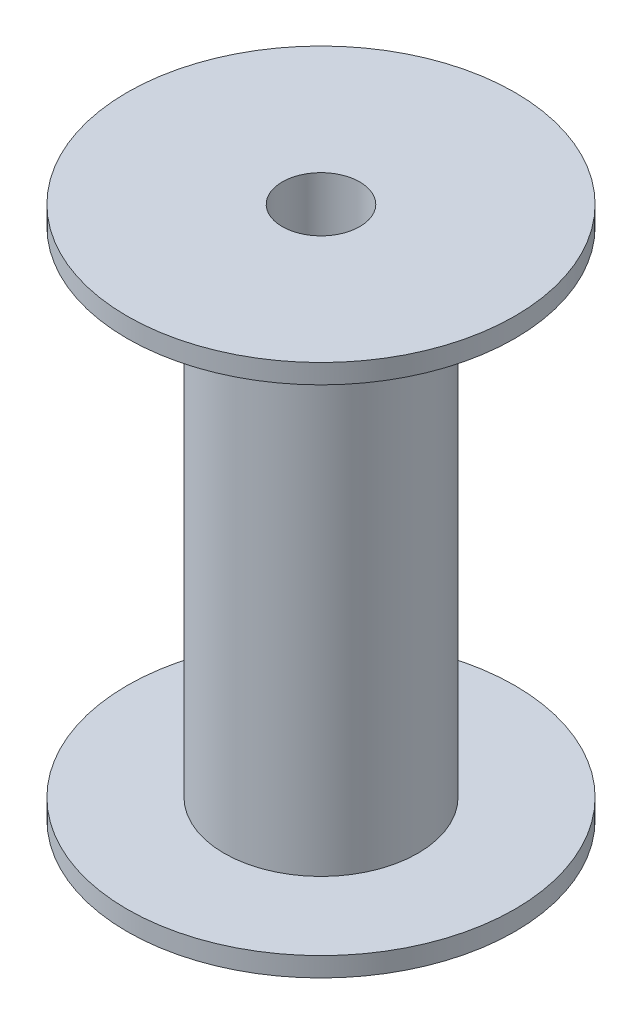
SolidWorks part; units mm, degrees
ref_plane "Front Plane" through (0, 0, 0) normal (0, 0, 1) x (1, 0, 0)
ref_plane "Top Plane" through (0, 0, 0) normal (0, 1, 0) x (1, 0, 0)
ref_plane "Right Plane" through (0, 0, 0) normal (1, 0, 0) x (0, 0, -1)
sketch "Sketch1" plane through (0, 0, 0) normal (0, 1, 0) x (1, 0, 0)
  circle A0 centre (0, 0) radius 4
  circle A1 centre (0, 0) radius 20
  dimension "D1" = 8
  dimension "D2" = 40
extrude "Boss-Extrude1" add sketch "Sketch1" along normal blind 55
sketch "Sketch2" plane through (0, 55, 0) normal (0, 1, 0) x (1, 0, 0)
  circle A0 centre (0, 0) radius 10
  circle A1 centre (0, 0) radius 20 construction
  circle A2 centre (0, 0) radius 20
  dimension "D1" = 10
extrude "Cut-Extrude4" cut sketch "Sketch2" against normal blind 51 from offset 2 offset against normal yes
